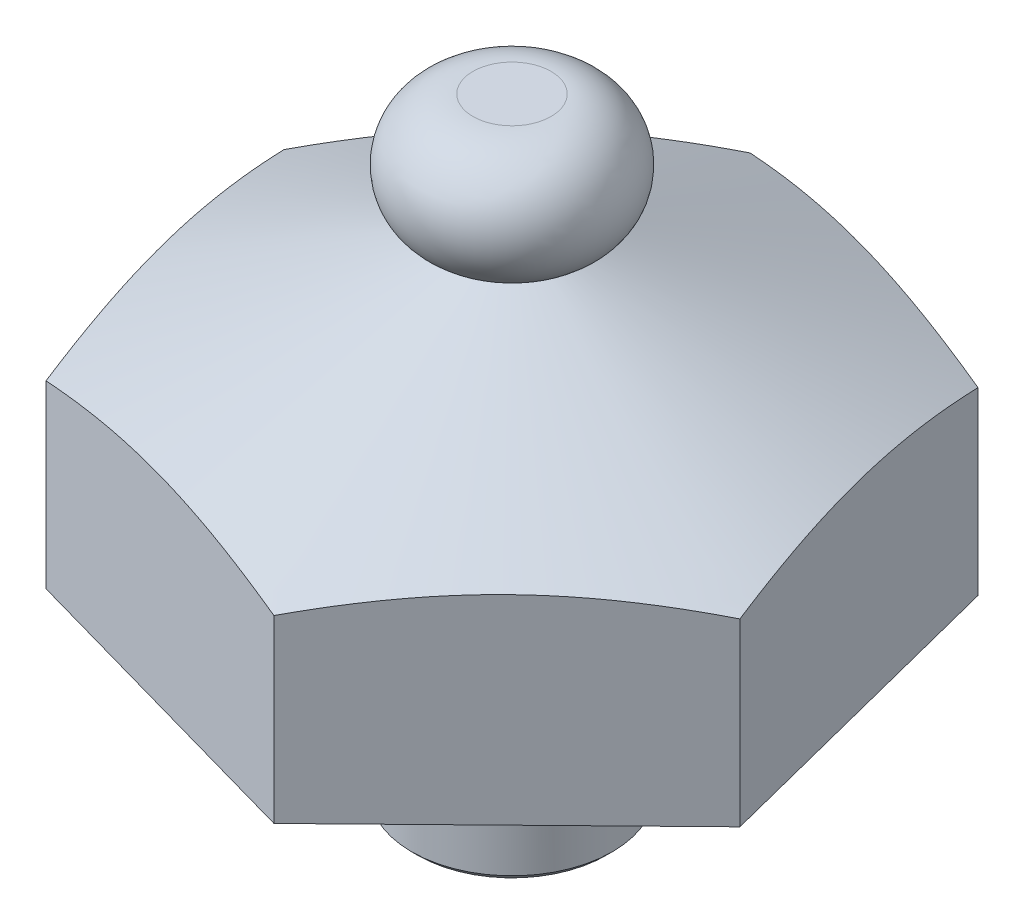
SolidWorks part; units mm, degrees
ref_plane "Front Plane" through (0, 0, 0) normal (0, 0, 1) x (1, 0, 0)
ref_plane "Top Plane" through (0, 0, 0) normal (0, 1, 0) x (1, 0, 0)
ref_plane "Right Plane" through (0, 0, 0) normal (1, 0, 0) x (0, 0, -1)
sketch "Sketch1" plane through (0, 0, 0) normal (0, 0, 1) x (1, 0, 0)
  line L0 (0, 0) -> (0, 100) construction
  line L1 (0, 100) -> (-6.38, 100)
  line L2 (-6.38, 80) -> (-53.8141, 58.9459)
  line L3 (-53.8141, 58.9459) -> (-53.8141, 29.5423)
  line L4 (-53.8141, 29.5423) -> (-16.38, 29.5423)
  line L5 (-16.38, 29.5423) -> (-16.38, 0)
  line L6 (-16.38, 0) -> (0, 0)
  line L7 (0, 0) -> (0, 100)
  arc A0 (-6.38, 100) -> (-6.38, 80) centre (-6.38, 90) ccw
  dimension "D2" = 10
  dimension "D1" = 100
  dimension "D3" = 51.8967
  dimension "D4" = 29.4036
  dimension "D5" = 37.4341
  dimension "D6" = 29.5423
  dimension "D7" = 6.38
revolve "Revolve1" add sketch "Sketch1" angle 360 about L0
sketch "Sketch2" plane through (0, 100, 0) normal (0, 1, 0) x (1, 0, 0)
  line L1 (-38.5273, -37.5714) -> (13.2742, -52.1513)
  line L2 (13.2742, -52.1513) -> (51.8014, -14.5799)
  line L3 (51.8014, -14.5799) -> (38.5273, 37.5714)
  line L4 (38.5273, 37.5714) -> (-13.2742, 52.1513)
  line L5 (-13.2742, 52.1513) -> (-51.8014, 14.5799)
  line L6 (-51.8014, 14.5799) -> (-38.5273, -37.5714)
  circle A0 centre (0, 0) radius 46.6044 construction
  dimension "D1" = 53.8141
extrude "Cut-Extrude1" cut sketch "Sketch2" against normal through all flip side to cut
chamfer "Chamfer1" distance 1 angle 45 1 edges at (0, 0, -16.38)
